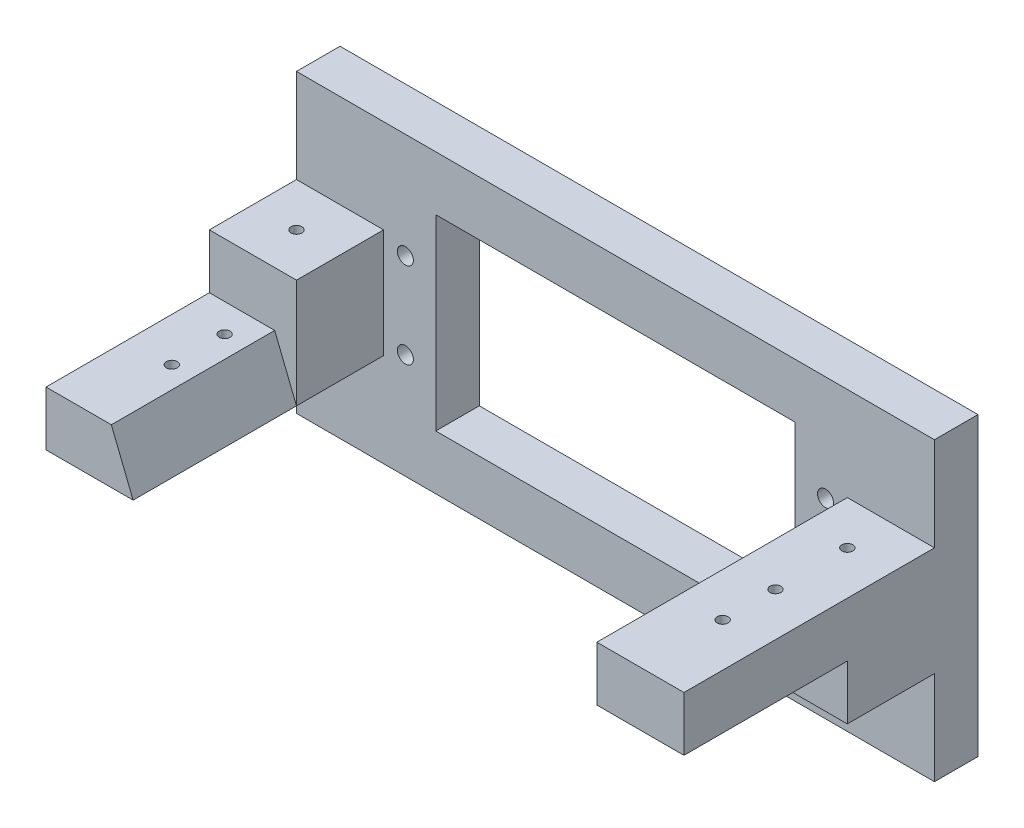
SolidWorks part; units mm, degrees
ref_plane "Front Plane" through (0, 0, 0) normal (0, 0, 1) x (1, 0, 0)
ref_plane "Top Plane" through (0, 0, 0) normal (0, 1, 0) x (1, 0, 0)
ref_plane "Right Plane" through (0, 0, 0) normal (1, 0, 0) x (0, 0, -1)
sketch "Sketch1" plane through (0, 0, 0) normal (0, 0, 1) x (1, 0, 0)
  line L1 (0, 0) -> (54.61, 0)
  line L2 (0, 0) -> (0, 47.244)
  line L3 (0, 47.244) -> (54.61, 47.244)
  line L4 (54.61, 0) -> (54.61, 47.244)
  line L5 (6.35, 12.7) -> (48.26, 12.7)
  line L6 (6.35, 12.7) -> (6.35, 34.544)
  line L7 (6.35, 34.544) -> (48.26, 34.544)
  line L8 (48.26, 12.7) -> (48.26, 34.544)
  dimension "D1" = 41.91
  dimension "D2" = 21.844
  dimension "D3" = 6.35
  dimension "D4" = 6.35
  dimension "D5" = 12.7
  dimension "D6" = 12.7
extrude "Boss-Extrude1" add sketch "Sketch1" along normal blind 5.08
sketch "Sketch2" plane through (0, 0, 5.08) normal (0, 0, 1) x (1, 0, 0)
  line L0 (0, 23.622) -> (54.61, 23.622) construction
  line L1 (2.8054, 28.622) -> (51.8046, 28.622) construction
  line L2 (2.8054, 28.622) -> (2.8054, 18.622) construction
  line L3 (2.8054, 18.622) -> (51.8046, 18.622) construction
  line L4 (51.8046, 28.622) -> (51.8046, 18.622) construction
  line L5 (0, 47.244) -> (0, 0) construction
  line L6 (54.61, 0) -> (54.61, 47.244) construction
  line L7 (2.8054, 23.622) -> (51.8046, 23.622) construction
  line L8 (27.305, 28.622) -> (27.305, 18.622) construction
  line L9 (27.305, 47.244) -> (27.305, 0) construction
  line L10 (54.61, 47.244) -> (0, 47.244) construction
  line L11 (0, 0) -> (54.61, 0) construction
  line L12 (25.1752, 42.164) -> (29.4348, 42.164) construction
  line L13 (29.4348, 42.164) -> (29.4348, 5.08) construction
  line L14 (29.4348, 5.08) -> (25.1752, 5.08) construction
  line L15 (25.1752, 5.08) -> (25.1752, 42.164) construction
  line L16 (48.26, 34.544) -> (6.35, 34.544) construction
  line L17 (6.35, 12.7) -> (48.26, 12.7) construction
  circle A0 centre (2.8054, 28.622) radius 0.936
  circle A1 centre (2.8054, 18.622) radius 0.936
  circle A2 centre (51.8046, 28.622) radius 0.936
  circle A3 centre (51.8046, 18.622) radius 0.936
  circle A4 centre (25.1752, 5.08) radius 0.635 construction
  circle A5 centre (29.4348, 5.08) radius 0.635 construction
  circle A6 centre (29.4348, 42.164) radius 0.635 construction
  circle A7 centre (25.1752, 42.164) radius 0.635 construction
  point P16 (2.8054, 27.686)
  point P17 (2.8054, 19.558)
  dimension "D2" = 8.128
  dimension "D4" = 1.872
  dimension "D5" = 1.27
  dimension "D1" = 10
  dimension "D3" = 48.9991
  dimension "D6" = 4.2596
  dimension "D7" = 2.1298
  dimension "D8" = 7.62
  dimension "D9" = 7.62
  dimension "D10" = 37.084
extrude "Cut-Extrude1" cut sketch "Sketch2" against normal through all
sketch "Sketch10" plane through (0, 0, 5.08) normal (0, 0, 1) x (1, 0, 0)
  line L0 (0, 47.244) -> (0, 80.7756)
  line L1 (0, 80.7756) -> (-31.1018, 80.7756)
  line L2 (0, 47.244) -> (0, 0)
  line L3 (-31.1018, 80.7756) -> (-31.1018, -10.4159)
  line L4 (-31.1018, -10.4159) -> (0, -10.4159)
  line L5 (0, 23.622) -> (54.61, 23.622) construction
  line L6 (54.61, 0) -> (54.61, 47.244) construction
  line L7 (54.61, 23.622) -> (62.23, 23.622) construction
  line L8 (62.23, 23.622) -> (66.4896, 23.622)
  line L9 (-13.8825, 79.8399) -> (-11.43, 79.8399)
  line L10 (-13.8825, 79.8399) -> (-13.8825, 3.6399)
  line L11 (-13.8825, 3.6399) -> (-11.43, 3.6399)
  line L12 (-11.43, 79.8399) -> (-11.43, 3.6399)
  line L13 (0, -10.4159) -> (0, 47.244)
  line L14 (69.0296, 23.622) -> (66.4896, 23.622) construction
  line L15 (0, 47.244) -> (0, 0) construction
  line L16 (64.3598, 25.7518) -> (64.3598, 21.4922) construction
  line L17 (54.61, 33.3718) -> (69.0296, 33.3718)
  line L18 (54.61, 33.3718) -> (54.61, 13.8722)
  line L19 (54.61, 13.8722) -> (69.0296, 13.8722)
  line L20 (69.0296, 33.3718) -> (69.0296, 13.8722)
  line L21 (0, 0) -> (54.61, 0) construction
  line L23 (54.61, 13.1354) -> (54.5843, 13.1354)
  circle A0 centre (-6.7996, 44.704) radius 0.635
  circle A1 centre (-2.54, 44.704) radius 0.635
  circle A2 centre (62.23, 23.622) radius 0.635 construction
  circle A3 centre (66.4896, 23.622) radius 0.635 construction
  circle A4 centre (64.3598, 25.7518) radius 0.635
  circle A5 centre (64.3598, 21.4922) radius 0.635
  point P27 (64.3598, 23.622)
  dimension "D1" = 1.27
  dimension "D10" = 13.8825
  dimension "D11" = 31.1018
  dimension "D2" = 4.2596
  dimension "D3" = 7.62
  dimension "D4" = 2.54
  dimension "D5" = 7.62
  dimension "D6" = 76.2
  dimension "D7" = 2.54
  dimension "D8" = 11.43
  dimension "D9" = 54.5843
  dimension "D12" = 3.6399
  dimension "D13" = 13.1354
  dimension "D14" = 44.704
  dimension "D15" = 80.7756
  dimension "D16" = 10.4159
  dimension "D17" = 4.2596
extrude "Boss-Extrude4" add sketch "Sketch10" against normal up to surface (5.08 mm away)
sketch "Sketch11" plane through (0, 0, 5.08) normal (0, 0, 1) x (1, 0, 0)
  line L0 (0, 47.244) -> (-5.842, 47.244)
  line L1 (-5.842, 47.244) -> (-5.842, 64.262)
  line L2 (-5.842, 64.262) -> (-15.748, 64.262)
  line L3 (-15.748, 64.262) -> (-15.748, -17.018)
  line L4 (-15.748, -17.018) -> (-4.572, -17.018)
  line L5 (-4.572, -17.018) -> (-4.572, 0)
  line L6 (-4.572, 0) -> (0, 0)
  line L7 (0, 0) -> (0, 47.244)
  line L11 (-9.144, 61.722) -> (-5.842, 61.722) construction
  line L12 (-12.446, 61.722) -> (-9.144, 61.722)
  line L13 (-12.446, 61.722) -> (-12.446, -14.478)
  line L14 (-12.446, -14.478) -> (-9.144, -14.478)
  line L15 (-9.144, 61.722) -> (-9.144, -14.478)
  line L16 (-12.446, 61.722) -> (-15.748, 61.722) construction
  line L17 (-12.446, 61.722) -> (-12.446, 64.262) construction
  line L18 (-12.446, -14.478) -> (-12.446, -17.018) construction
  line L19 (0, 47.244) -> (0, 0) construction
  line L20 (0, 0) -> (54.61, 0) construction
  circle A0 centre (64.3598, 25.7518) radius 0.635 construction
  circle A1 centre (64.3598, 21.4922) radius 0.635 construction
  circle A2 centre (64.3598, 25.7518) radius 0.635 construction
  circle A3 centre (64.3598, 21.4922) radius 0.635 construction
  circle A4 centre (-4.572, 21.4922) radius 0.635
  circle A5 centre (-4.572, 25.7518) radius 0.635
  dimension "D10" = 1.27
  dimension "D1" = 76.2
  dimension "D2" = 4.572
  dimension "D3" = 4.572
  dimension "D4" = 3.302
  dimension "D5" = 3.302
  dimension "D6" = 81.28
  dimension "D7" = 15.748
  dimension "D8" = 4.572
  dimension "D9" = 0
  dimension "D11" = 4.2596
  dimension "D12" = 4.572
  dimension "D13" = 21.4922
extrude "Boss-Extrude5" add sketch "Sketch11" against normal up to surface (5.08 mm away) up to face at (52.7406, 18.622, 0)
sketch "Sketch12" plane through (0, 0, 5.08) normal (0, 0, 1) x (1, 0, 0)
  line L0 (54.61, 33.3718) -> (54.61, 47.244) construction
  line L1 (-5.842, 47.244) -> (54.61, 47.244)
  line L2 (-5.842, 47.244) -> (-5.842, 40.894)
  line L3 (-5.842, 40.894) -> (54.61, 40.894)
  line L4 (54.61, 47.244) -> (54.61, 40.894)
  line L5 (54.61, 0) -> (54.61, 13.8722) construction
  line L6 (-4.572, 0) -> (54.61, 0)
  line L7 (-4.572, 0) -> (-4.572, 6.35)
  line L8 (-4.572, 6.35) -> (54.61, 6.35)
  line L9 (54.61, 0) -> (54.61, 6.35)
  line L10 (6.35, 12.7) -> (48.26, 12.7) construction
  line L11 (48.26, 34.544) -> (6.35, 34.544) construction
  line L12 (48.26, 12.7) -> (48.26, 34.544) construction
  line L13 (48.26, 12.7) -> (48.26, 34.544) construction
  dimension "D1" = 6.35
  dimension "D2" = 6.35
  dimension "D3" = 6.35
extrude "Cut-Extrude2" cut sketch "Sketch12" against normal through all
sketch "Sketch13" plane through (0, 0, 0) normal (0, 0, -1) x (-1, 0, 0)
  line L0 (15.748, 64.262) -> (15.748, -17.018) construction
  line L1 (7.1554, 62.8847) -> (14.175, 62.8847)
  line L2 (7.1554, 62.8847) -> (7.1554, -16.1087)
  line L3 (7.1554, -16.1087) -> (14.175, -16.1087)
  line L4 (14.175, 62.8847) -> (14.175, -16.1087)
  line L5 (9.144, 61.722) -> (12.446, 61.722) construction
  line L6 (12.446, -14.478) -> (9.144, -14.478) construction
  dimension "D1" = 7.0196
  dimension "D2" = 1.573
  dimension "D3" = 1.1627
  dimension "D4" = 1.6307
extrude "Boss-Extrude6" add sketch "Sketch13" against normal offset from surface (4.826 mm away) 0.254 up to face at (52.7406, 18.622, 5.08)
fillet "Fillet1" radius 2.54 12 edges at (69.0296, 13.8722, 2.54) (54.61, 6.35, 2.54) (-4.572, 6.35, 2.54) (-4.572, -17.018, 2.54) (-15.748, -17.018, 2.54) (-15.748, 64.262, 2.54) (-5.842, 64.262, 2.54) (-5.842, 40.894, 2.54) (54.61, 40.894, 2.54) (69.0296, 33.3718, 2.54)
sketch "Sketch14" plane through (0, 0, 5.08) normal (0, 0, 1) x (1, 0, 0)
  line L0 (2.8054, 28.622) -> (2.8054, 40.894) construction
  line L1 (-3.302, 40.894) -> (52.07, 40.894) construction
  line L2 (2.8054, 40.894) -> (-0.8159, 40.894)
  line L3 (-0.8159, 40.894) -> (-0.8159, 6.35)
  line L5 (52.07, 6.35) -> (-2.032, 6.35) construction
  line L6 (-0.8159, 6.35) -> (2.8054, 6.35)
  line L7 (2.8054, 6.35) -> (2.8054, -19.9418)
  line L8 (2.8054, -19.9418) -> (-23.5153, -19.9418)
  line L9 (-23.5153, -19.9418) -> (-23.5153, 65.8265)
  line L10 (-23.5153, 65.8265) -> (2.8054, 65.8265)
  line L11 (2.8054, 65.8265) -> (2.8054, 40.894)
  line L12 (51.8046, 28.622) -> (51.8046, 40.8969) construction
  line L13 (51.8046, 40.8969) -> (51.8046, 65.8265)
  line L14 (51.8046, 65.8265) -> (74.4862, 65.8265)
  line L15 (74.4862, 65.8265) -> (74.4862, -19.9418)
  line L16 (74.4862, -19.9418) -> (51.8046, -19.9418)
  line L17 (51.8046, -19.9418) -> (52.07, 6.35)
  line L18 (52.07, 6.35) -> (54.61, 8.89)
  line L19 (54.61, 8.89) -> (54.61, 38.354)
  line L20 (54.61, 38.354) -> (51.8046, 40.8969)
  line L21 (-15.748, 61.722) -> (-15.748, -14.478) construction
  line L22 (-8.382, 64.262) -> (-13.208, 64.262) construction
  dimension "D1" = 14.9321
  dimension "D2" = 90.2342
  dimension "D3" = 7.7673
  dimension "D4" = 1.5645
  dimension "D5" = 23.3651
  dimension "D6" = 84.2038
extrude "Cut-Extrude3" cut sketch "Sketch14" against normal through all
sketch "Sketch15" plane through (0, 0, 5.08) normal (0, 0, 1) x (1, 0, 0)
  line L0 (-0.8159, 40.894) -> (-9.8946, 40.894)
  line L1 (-9.8946, 40.894) -> (-9.8946, 6.35)
  line L2 (-9.8946, 6.35) -> (-0.8159, 6.35)
  line L3 (-0.8159, 6.35) -> (-0.8159, 40.894) construction
  line L4 (-0.8159, 6.35) -> (-0.8159, 40.894)
  line L5 (51.8077, 40.894) -> (54.61, 38.354)
  line L6 (54.61, 38.354) -> (54.61, 8.89)
  line L7 (54.61, 8.89) -> (54.61, 38.354) construction
  line L8 (54.61, 8.89) -> (52.07, 6.35)
  line L9 (52.07, 6.35) -> (64.5046, 6.35)
  line L10 (64.5046, 6.35) -> (64.5046, 40.894)
  line L11 (64.5046, 40.894) -> (51.8077, 40.894)
  circle A0 centre (2.8054, 28.622) radius 0.936 construction
  circle A1 centre (2.8054, 28.622) radius 0.936 construction
  circle A2 centre (51.8046, 28.622) radius 0.936 construction
  circle A3 centre (51.8046, 28.622) radius 0.936 construction
  dimension "D1" = 12.7
  dimension "D2" = 3.6214
  dimension "D3" = 12.7
extrude "Boss-Extrude7" add sketch "Sketch15" against normal up to surface (5.08 mm away) up to face at (35.2443, 21.1667, 0)
sketch "Sketch16" plane through (0, 0, 5.08) normal (0, 0, 1) x (1, 0, 0)
  line L0 (-9.8946, 40.894) -> (-9.8946, 6.35) construction
  line L1 (-9.8946, 17.272) -> (0.2654, 17.272)
  line L2 (-9.8946, 17.272) -> (-9.8946, 29.972)
  line L3 (-9.8946, 29.972) -> (0.2654, 29.972)
  line L4 (0.2654, 17.272) -> (0.2654, 29.972)
  line L5 (0.2654, 17.272) -> (54.3446, 17.272) construction
  line L6 (64.5046, 6.35) -> (64.5046, 40.894) construction
  line L7 (54.3446, 17.272) -> (64.5046, 17.272)
  line L8 (54.3446, 17.272) -> (54.3446, 29.972)
  line L9 (54.3446, 29.972) -> (64.5046, 29.972)
  line L10 (64.5046, 17.272) -> (64.5046, 29.972)
  line L11 (54.3446, 29.972) -> (0.2654, 29.972) construction
  line L12 (6.35, 23.622) -> (48.26, 23.622) construction
  line L13 (6.35, 34.544) -> (6.35, 12.7) construction
  line L14 (48.26, 12.7) -> (48.26, 34.544) construction
  line L15 (6.35, 23.622) -> (0.2654, 23.622) construction
  dimension "D1" = 10.16
  dimension "D2" = 12.7
extrude "Boss-Extrude8" add sketch "Sketch16" along normal blind 10.16
sketch "Sketch17" plane through (0, 29.972, 0) normal (0, 1, 0) x (1, 0, 0)
  line L0 (-4.8146, -10.16) -> (-4.8146, -5.08) construction
  line L4 (0.2654, -5.08) -> (-9.8946, -5.08) construction
  line L5 (59.4246, -5.08) -> (59.4246, -10.16) construction
  line L6 (64.5046, -5.08) -> (54.3446, -5.08) construction
  circle A0 centre (-4.8146, -10.16) radius 1.5875 construction
  circle A1 centre (-4.8146, -10.16) radius 0.635
  circle A2 centre (59.4246, -10.16) radius 0.635
  dimension "D1" = 3.175
  dimension "D2" = 1.27
  dimension "D5" = 1.27
  dimension "D3" = 5.08
  dimension "D4" = 5.08
extrude "Cut-Extrude4" cut sketch "Sketch17" against normal through all
ref_plane "Plane1" through (0, 0, 28.001) normal (0, 0, 1) x (1, 0, 0)
sketch "Sketch18" plane through (0, 0, 15.24) normal (0, 0, 1) x (1, 0, 0)
  line L0 (-9.8946, 23.622) -> (0.2654, 23.622) construction
  line L1 (-9.8946, 29.972) -> (-9.8946, 17.272) construction
  line L2 (0.2654, 17.272) -> (0.2654, 29.972) construction
  line L3 (0.2654, 23.622) -> (54.3446, 23.622) construction
  line L4 (54.3446, 29.972) -> (54.3446, 17.272) construction
  line L5 (54.3446, 23.622) -> (64.5046, 23.622) construction
  line L6 (64.5046, 17.272) -> (64.5046, 29.972) construction
  line L8 (-9.8946, 23.622) -> (0.2654, 23.622)
  line L9 (-9.8946, 23.622) -> (-9.8946, 17.272)
  line L10 (-9.8946, 17.272) -> (0.2654, 17.272)
  line L11 (0.2654, 23.622) -> (0.2654, 17.272)
  line L12 (54.3446, 23.622) -> (64.5046, 23.622)
  line L13 (54.3446, 23.622) -> (54.3446, 29.972)
  line L14 (54.3446, 29.972) -> (64.5046, 29.972)
  line L15 (64.5046, 23.622) -> (64.5046, 29.972)
extrude "Boss-Extrude9" add sketch "Sketch18" along normal up to surface (12.761 mm away) up to plane "Plane1"
sketch "Sketch19" plane through (0, 23.622, 0) normal (0, 1, 0) x (1, 0, 0)
  line L0 (-4.8146, -15.24) -> (-4.8146, -18.542) construction
  line L1 (-18.9992, -28.001) -> (18.9992, -28.001) construction
  line L2 (59.4246, -10.795) -> (59.4246, -28.001) construction
  line L3 (0.2654, -15.24) -> (-9.8946, -15.24) construction
  line L4 (-4.8146, -18.542) -> (-4.8146, -24.699) construction
  line L6 (-4.8146, -24.699) -> (-4.8146, -28.001) construction
  circle A0 centre (-4.8146, -10.16) radius 0.635 construction
  circle A1 centre (59.4246, -10.16) radius 0.635 construction
  circle A2 centre (-4.8146, -18.542) radius 0.635
  circle A3 centre (-4.8146, -24.699) radius 0.635
  circle A4 centre (59.4246, -18.542) radius 0.635
  circle A5 centre (59.4246, -24.699) radius 0.635
  circle A6 centre (-4.8146, -10.16) radius 0.635 construction
  dimension "D1" = 1.27
  dimension "D2" = 3.302
  dimension "D3" = 3.302
  dimension "D4" = 6.157
  dimension "D5" = 3.302
  dimension "D6" = 6.157
extrude "Cut-Extrude5" cut sketch "Sketch19" against normal through all and the other way through all
sketch "Sketch20" plane through (0, 0, 28.001) normal (0, 0, 1) x (1, 0, 0)
  line L0 (0.2654, 23.622) -> (-9.8946, 23.622) construction
  line L1 (0.2654, 17.272) -> (0.2654, 23.622) construction
  line L2 (-9.8946, 17.272) -> (0.2654, 17.272) construction
  line L3 (-9.8946, 23.622) -> (-9.8946, 17.272) construction
  line L4 (54.3446, 29.972) -> (54.3446, 23.622) construction
  line L5 (64.5046, 29.972) -> (54.3446, 29.972) construction
  line L6 (64.5046, 23.622) -> (64.5046, 29.972) construction
  line L7 (54.3446, 23.622) -> (64.5046, 23.622) construction
  line L8 (0.2654, 23.622) -> (-9.8946, 23.622)
  line L9 (0.2654, 17.272) -> (0.2654, 23.622)
  line L10 (-9.8946, 17.272) -> (0.2654, 17.272)
  line L11 (-9.8946, 23.622) -> (-9.8946, 17.272)
  line L12 (54.3446, 29.972) -> (54.3446, 23.622)
  line L13 (64.5046, 29.972) -> (54.3446, 29.972)
  line L14 (64.5046, 23.622) -> (64.5046, 29.972)
  line L15 (54.3446, 23.622) -> (64.5046, 23.622)
extrude "Boss-Extrude10" add sketch "Sketch20" along normal blind 6.289
sketch "Sketch22" plane through (0, 0, 34.29) normal (0, 0, 1) x (1, 0, 0)
  line L0 (0.2654, 17.272) -> (-2.2746, 23.622)
  line L1 (0.2654, 23.622) -> (-9.8946, 23.622) construction
  line L2 (-2.2746, 23.622) -> (0.2654, 23.622)
  line L3 (0.2654, 17.272) -> (0.2654, 29.972) construction
  line L4 (0.2654, 23.622) -> (0.2654, 17.272)
  dimension "D1" = 2.54
extrude "Cut-Extrude7" cut sketch "Sketch22" against normal up to surface (19.05 mm away) up to face at (-3.5446, 26.797, 15.24)
equation "\"D7@Sketch2\"=\"D6@Sketch2\"/2"
equation "\"D8@Sketch11\" = \"D2@Sketch11\""
equation "\"D1@Sketch12\"=\"D3@Sketch12\""
equation "\"D2@Sketch12\"= \"D1@Sketch12\""
equation "\"D3@Sketch11\"= \"D2@Sketch11\""
equation "\"D5@Sketch17\"=\"D2@Sketch17\""
equation "\"D5@Sketch19\"=\"D3@Sketch19\""
equation "\"D6@Sketch19\"=\"D4@Sketch19\""
